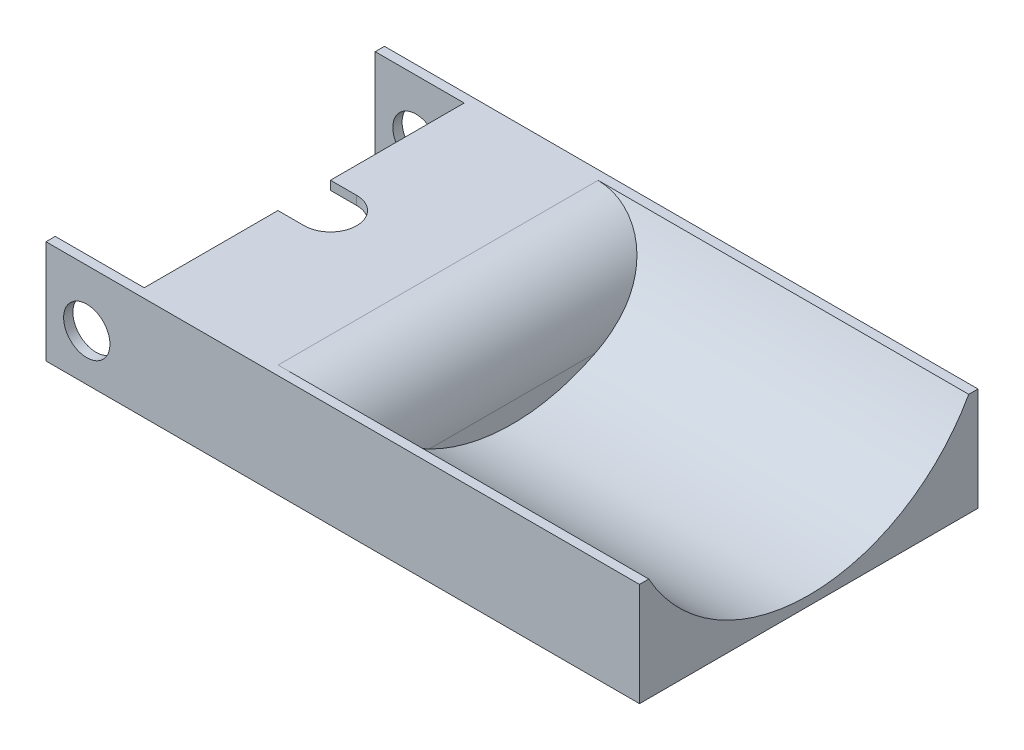
SolidWorks part; units mm, degrees
ref_plane "Front Plane" through (0, 0, 0) normal (0, 0, 1) x (1, 0, 0)
ref_plane "Top Plane" through (0, 0, 0) normal (0, 1, 0) x (1, 0, 0)
ref_plane "Right Plane" through (0, 0, 0) normal (1, 0, 0) x (0, 0, -1)
sketch "Sketch1" plane through (0, 0, 0) normal (1, 0, 0) x (0, 0, -1)
  line L1 (28.9941, 8.8506) -> (-28.9941, 8.8506)
  line L2 (28.9941, 8.8506) -> (28.9941, -8.8506)
  line L3 (28.9941, -8.8506) -> (-28.9941, -8.8506)
  line L4 (-28.9941, 8.8506) -> (-28.9941, -8.8506)
  line L5 (28.9941, 8.8506) -> (-28.9941, -8.8506) construction
  line L6 (28.9941, -8.8506) -> (-28.9941, 8.8506) construction
  point P0 (0, 0)
  dimension "D1" = 57.9882
  dimension "D2" = 17.7013
extrude "Boss-Extrude1" add sketch "Sketch1" along normal blind 101.6816 contours L1 L4 L3 L2
sketch "Sketch3" plane through (0, 8.8506, 0) normal (0, 1, 0) x (1, 0, 0)
  line L2 (0, 28.9941) -> (15.24, 28.9941)
  line L3 (0, 28.9941) -> (0, 27.4066)
  line L4 (0, 27.4066) -> (15.24, 27.4066)
  line L5 (15.24, 28.9941) -> (15.24, 27.4066)
  line L6 (0, -28.9941) -> (15.24, -28.9941)
  line L7 (0, -28.9941) -> (0, -27.4066)
  line L8 (0, -27.4066) -> (15.24, -27.4066)
  line L9 (15.24, -28.9941) -> (15.24, -27.4066)
  point P11 (0, 0)
  point P12 (0, 0)
  dimension "D1" = 15.24
  dimension "D2" = 1.5875
  dimension "D3" = 15.24
  dimension "D4" = 1.5875
sketch "Sketch5" plane through (0, 8.8506, 0) normal (0, 1, 0) x (1, 0, 0)
  line L1 (0, 27.4066) -> (15.24, 27.4066)
  line L2 (0, 27.4066) -> (0, -27.4066)
  line L3 (0, -27.4066) -> (15.24, -27.4066)
  line L4 (15.24, 27.4066) -> (15.24, -27.4066)
extrude "Cut-Extrude1" cut sketch "Sketch5" against normal blind 127
sketch "Sketch6" plane through (0, 8.8506, 0) normal (0, 1, 0) x (1, 0, 0)
  line L1 (15.24, -27.4066) -> (15.24, 27.4066) construction
  line L4 (19.7396, 4.4996) -> (15.24, 4.4996)
  line L5 (19.7396, -4.4996) -> (15.24, -4.4996)
  circle A0 centre (19.7396, 0) radius 4.4996
  point P6 (127, 0)
  line M5 (15.24, 27.4066) -> (15.24, -27.4066)
  dimension "D1" = 8.9992
extrude "Cut-Extrude2" cut sketch "Sketch6" against normal blind 127 contours A0 L4 M5 | A0 | A0 L5 M5
sketch "Sketch7" plane through (101.6816, 0, 0) normal (1, 0, 0) x (0, 0, -1)
  line L0 (-27.4066, 8.8506) -> (-27.4066, -8.8506)
  line L1 (28.9941, -8.8506) -> (-28.9941, -8.8506) construction
  line L2 (27.4066, 8.8506) -> (27.4066, -8.8506)
  line L3 (28.9941, 8.8506) -> (27.4066, 8.8506) construction
  line L4 (28.9941, 8.8506) -> (-28.9941, 8.8506) construction
  line L5 (-27.4066, -7.2631) -> (27.4066, -7.2631)
  line L6 (-27.4066, 7.2631) -> (27.4066, 7.2631)
  line L8 (28.9941, 8.8506) -> (28.9941, -8.8506) construction
  arc A2 (-27.4066, 8.8506) -> (27.4066, 8.8506) centre (0, 24.1006) ccw
  line M4 (28.9941, 8.8506) -> (-28.9941, 8.8506)
  dimension "D1" = 1.5875
  dimension "D2" = 1.5875
  dimension "D3" = 1.5875
extrude "Cut-Extrude13" cut sketch "Sketch7" against normal blind 50.8 contours L0 L6 L2 M4 | L6 A2
fillet "Fillet5" radius 12.7 1 edges at (50.8816, 8.8506, 0)
sketch "Sketch14" plane through (0, 0, -28.9941) normal (0, 0, -1) x (-1, 0, 0)
  line L2 (0, 8.8506) -> (-15.24, 8.8506) construction
  line L3 (0, 8.8506) -> (0, -8.8506) construction
  circle A0 centre (-6.985, -0.8903) radius 3.9688
  dimension "D1" = 7.9375
  dimension "D2" = 9.7409
  dimension "D3" = 6.985
extrude "Cut-Extrude14" cut sketch "Sketch14" against normal blind 88.9
sketch "Sketch18" plane through (0, -8.8506, 0) normal (0, -1, 0) x (1, 0, 0)
  line L0 (38.1813, 27.4066) -> (38.1813, -27.4066)
  line L1 (38.1813, 27.4066) -> (15.24, 27.4066)
  line L2 (38.1813, -27.4066) -> (15.24, -27.4066)
  line L25 (15.24, -27.4066) -> (15.24, -4.4996) construction
  line L28 (15.24, -27.4066) -> (15.24, -4.4996)
extrude "Cut-Extrude16" cut sketch "Sketch18" against normal blind 16.1925 and the other way through all
